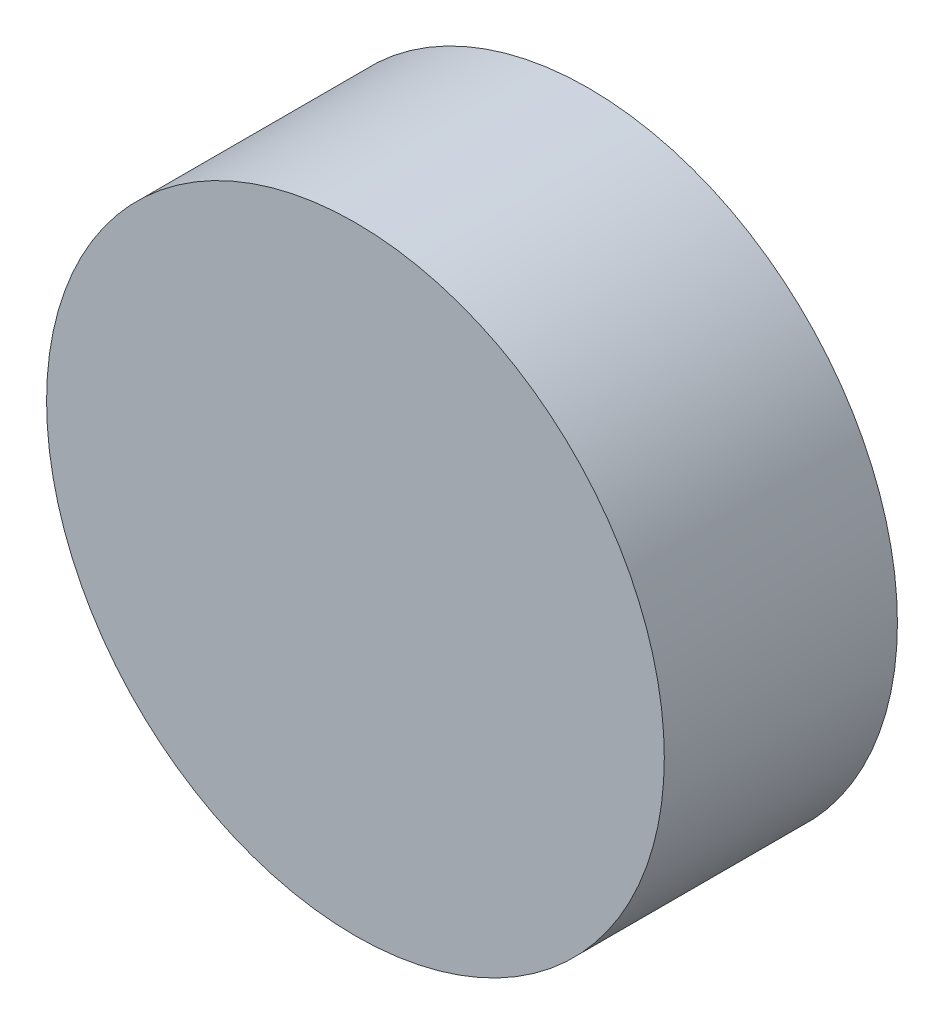
SolidWorks part; units mm, degrees
material "PET"
ref_plane "Front Plane" through (0, 0, 0) normal (0, 0, 1) x (1, 0, 0)
ref_plane "Top Plane" through (0, 0, 0) normal (0, 1, 0) x (1, 0, 0)
ref_plane "Right Plane" through (0, 0, 0) normal (1, 0, 0) x (0, 0, -1)
sketch "Sketch1" plane through (0, 0, 0) normal (0, 0, 1) x (1, 0, 0)
  circle A0 centre (0, 0) radius 26.5
  dimension "D1" = 53
extrude "Boss-Extrude1" add sketch "Sketch1" along normal blind 20
